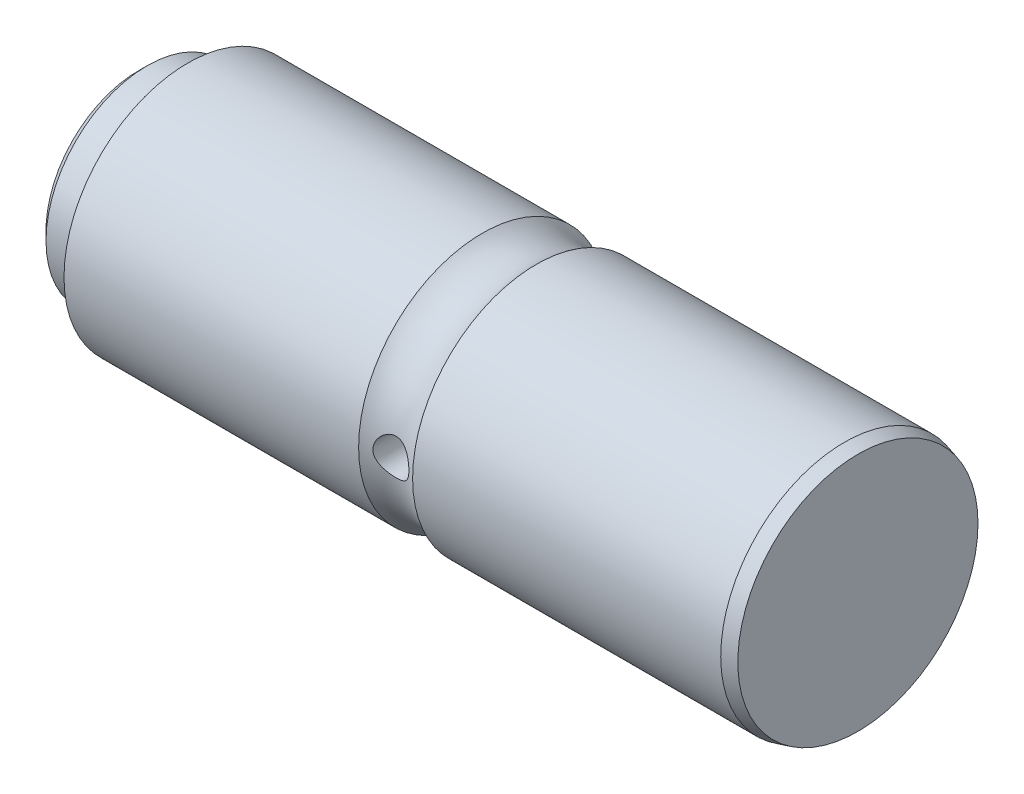
SolidWorks part; units mm, degrees
material "45"
ref_plane "前视基准面" through (0, 0, 0) normal (0, 0, 1) x (1, 0, 0)
ref_plane "上视基准面" through (0, 0, 0) normal (0, 1, 0) x (1, 0, 0)
ref_plane "右视基准面" through (0, 0, 0) normal (1, 0, 0) x (0, 0, -1)
sketch "草图1" plane through (0, 0, 0) normal (0, 0, 1) x (1, 0, 0)
  line L0 (0, 0) -> (-164.3687, 0) construction
  line L2 (0, 0) -> (0, 27.5)
  line L9 (-83.5, 27.5) -> (-149, 27.5)
  line L10 (-149, 27.5) -> (-149, 22.5)
  line L11 (-149, 22.5) -> (-160, 22.5)
  line L12 (-160, 22.5) -> (-160, 0)
  line L13 (-160, 0) -> (0, 0)
  line L17 (0, 27.5) -> (-71.5, 27.5)
  arc A1 (-83.5, 27.5) -> (-71.5, 27.5) centre (-77.5, 35.5) ccw
  dimension "D1" = 55
  dimension "D5" = 10
  dimension "D7" = 8
  dimension "D8" = 71.5
  dimension "D2" = 45
  dimension "D3" = 160
  dimension "D4" = 11
revolve "旋转1" add sketch "草图1" angle 360 about L0
sketch "草图2" plane through (0, 0, 0) normal (0, 0, 1) x (1, 0, 0)
  line L0 (-77.5, 25.5) -> (-77.5, -25.5) construction
  circle A2 centre (-77.5, 0) radius 4
  arc A3 (-83.5, 27.5) -> (-71.5, 27.5) centre (-77.5, 35.5) ccw construction
  arc A4 (-71.5, -27.5) -> (-83.5, -27.5) centre (-77.5, -35.5) ccw construction
  dimension "D1" = 8
extrude "切除-拉伸1" cut sketch "草图2" against normal mid plane 60
chamfer "倒角1" distance 2 angle 45 1 edges at (-160, 0, -22.5)
chamfer "倒角2" distance 3 angle 15 1 edges at (0, 0, -27.5)
sketch "草图6" plane through (-160, 0, 0) normal (-1, 0, 0) x (0, 0, 1)
  circle A0 centre (0, 0) radius 15
  dimension "D1" = 30
extrude "切除-拉伸3" cut sketch "草图6" against normal blind 10
hole_wizard "Ø8.0 (8) 直径孔1" positions "3D草图3" profile "草图7" hole size "Ø8.0" standard "GB"
sketch3d "3D草图3"
  line L0 (-150, 0, 0) -> (-160, 0, 0) construction
  point P0 (-150, 0, 0)
sketch "草图7" plane through (-150, 0, 0) normal (0, 1, 0) x (0, 0, 1)
  line L0 (0, 0) -> (0, 82.4034)
  line L1 (0, 82.4034) -> (4, 80)
  line L2 (4, 80) -> (4, 0)
  line L5 (4, 0) -> (0, 0)
  line L10 (0, 82.4034) -> (-4, 80) construction
  line L11 (0, -6.35) -> (0, 107.95) construction
  dimension "孔直径" = 8
  dimension "孔深度" = 80
  dimension "导头角度" = 118
hole_wizard "M10x1.0 螺纹孔1" positions "草图8" profile "草图9" tap size "M10x1.0" standard "GB"
sketch "草图8" plane through (-150, 0, 0) normal (-1, 0, 0) x (0, 0, 1)
  point P0 (0, 0)
sketch "草图9" plane through (-150, 0, 0) normal (0, 1, 0) x (0, 0, 1)
  line L0 (0, 0) -> (0, 17.7039)
  line L1 (0, 17.7039) -> (4.5, 15)
  line L2 (4.5, 15) -> (4.5, 0)
  line L5 (4.5, 0) -> (0, 0)
  line L10 (0, 17.7039) -> (-4.5, 15) construction
  line L11 (0, -6.35) -> (0, 107.95) construction
  dimension "螺纹孔钻头直径" = 9
  dimension "螺纹孔钻头深度" = 15
  dimension "导头角度" = 118
cosmetic thread "孔螺蚊线1" parameters "D1"=12, "D2"=10
